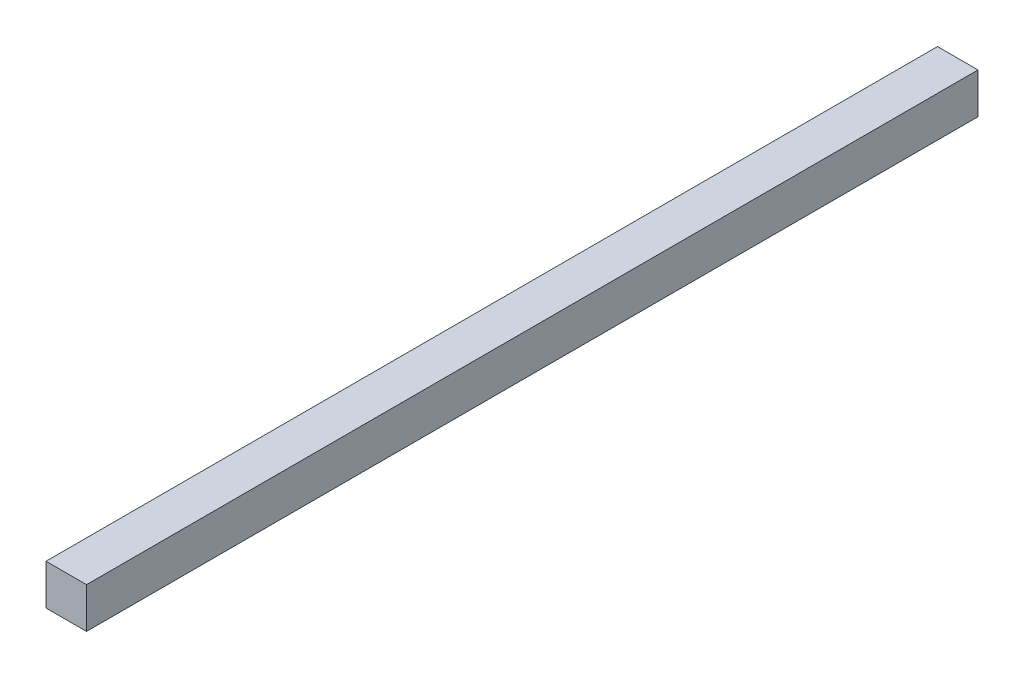
SolidWorks part; units mm, degrees
ref_plane "Front Plane" through (0, 0, 0) normal (0, 0, 1) x (1, 0, 0)
ref_plane "Top Plane" through (0, 0, 0) normal (0, 1, 0) x (1, 0, 0)
ref_plane "Right Plane" through (0, 0, 0) normal (1, 0, 0) x (0, 0, -1)
other "Configuration Table"
sketch "Sketch1" plane through (0, 0, 0) normal (0, 0, 1) x (1, 0, 0)
  line L1 (330, 1300) -> (350, 1300)
  line L2 (330, 1300) -> (330, 1320)
  line L3 (330, 1320) -> (350, 1320)
  line L4 (350, 1300) -> (350, 1320)
extrude "PRESS_kova_kizagi_sag_1" add sketch "Sketch1" against normal blind 440 from offset 60 separate body
